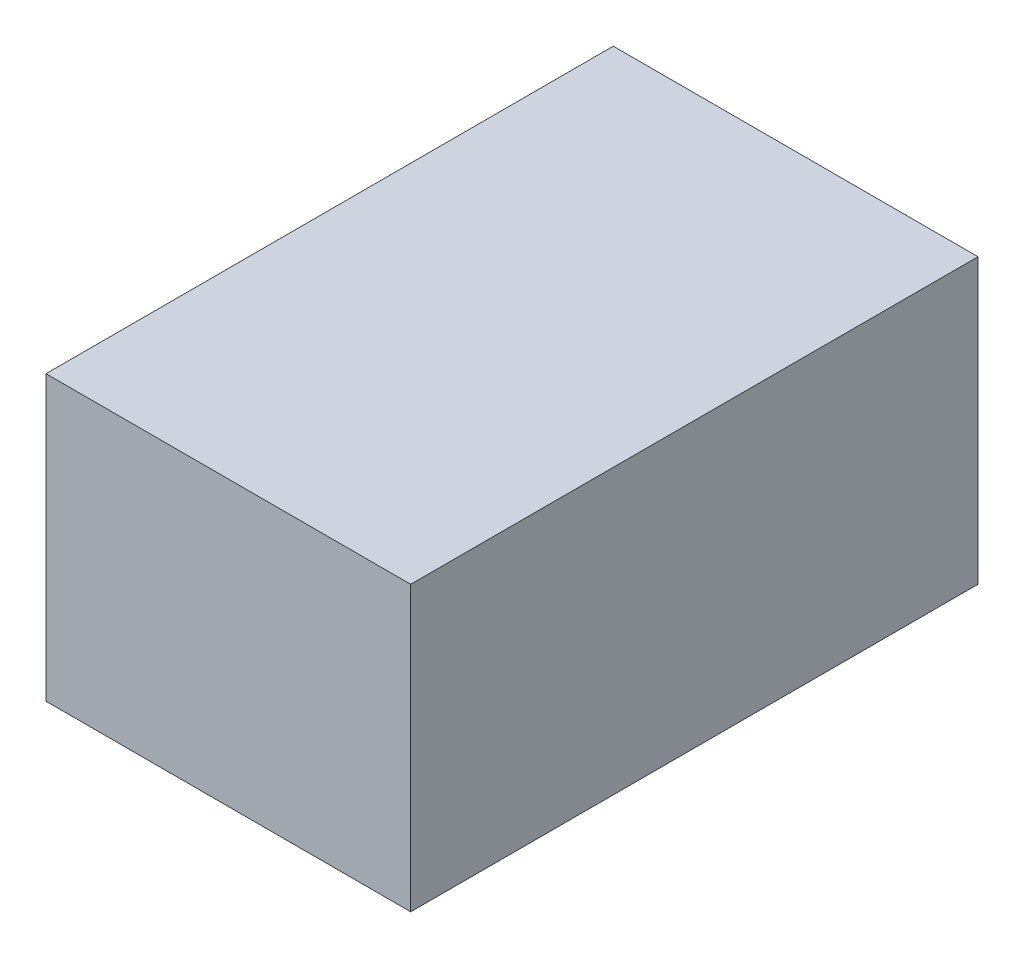
SolidWorks part; units mm, degrees
ref_plane "Front Plane" through (0, 0, 0) normal (0, 0, 1) x (1, 0, 0)
ref_plane "Top Plane" through (0, 0, 0) normal (0, 1, 0) x (1, 0, 0)
ref_plane "Right Plane" through (0, 0, 0) normal (1, 0, 0) x (0, 0, -1)
sketch "Sketch1" plane through (0, 0, 0) normal (0, 1, 0) x (1, 0, 0)
  line L1 (-45, -70) -> (45, -70)
  line L2 (-45, -70) -> (-45, 70)
  line L3 (-45, 70) -> (45, 70)
  line L4 (45, -70) -> (45, 70)
  line L5 (-45, -70) -> (45, 70) construction
  line L6 (-45, 70) -> (45, -70) construction
  point P0 (0, 0)
  dimension "D1" = 140
  dimension "D2" = 90
extrude "Boss-Extrude1" add sketch "Sketch1" along normal blind 70
